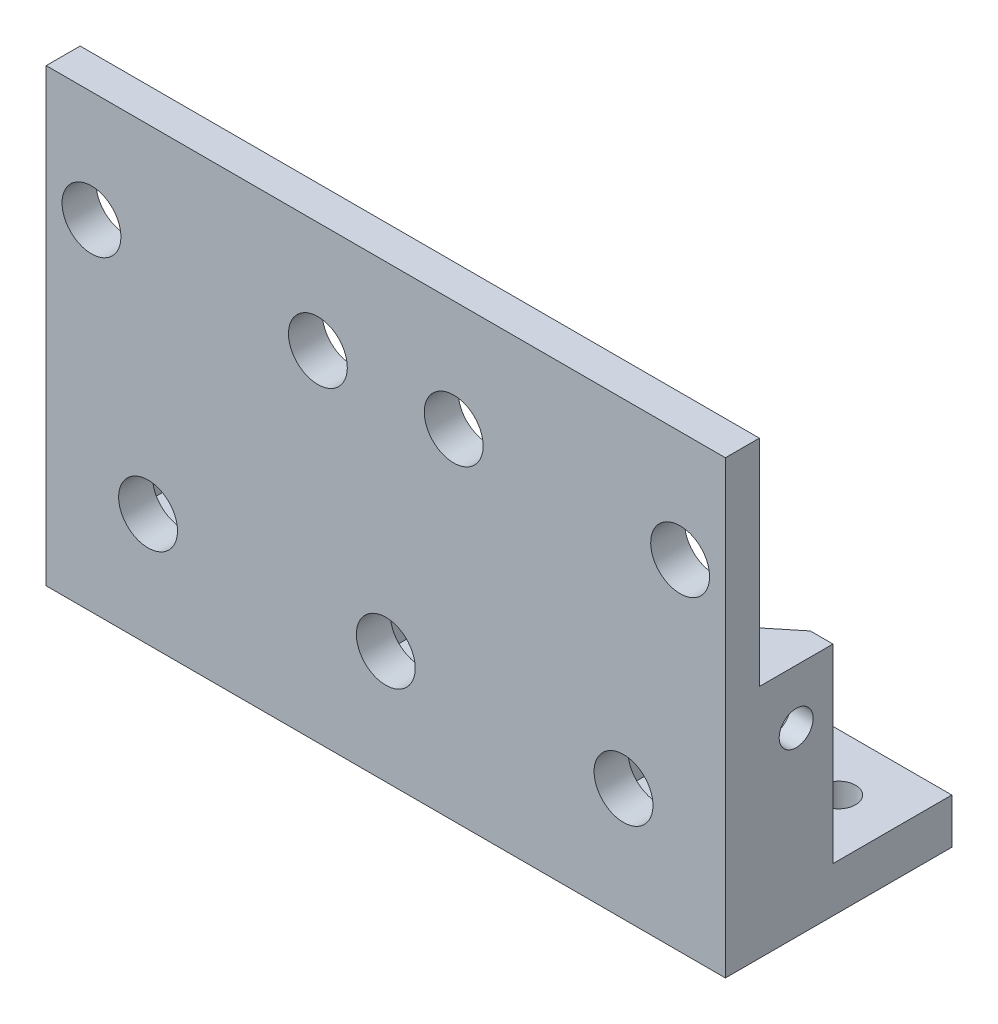
SolidWorks part; units mm, degrees
ref_plane "前视基准面" through (0, 0, 0) normal (0, 0, 1) x (1, 0, 0)
ref_plane "上视基准面" through (0, 0, 0) normal (0, 1, 0) x (1, 0, 0)
ref_plane "右视基准面" through (0, 0, 0) normal (1, 0, 0) x (0, 0, -1)
other "Configuration Table"
sketch "草图1" plane through (0, 0, 0) normal (1, 0, 0) x (0, 0, -1)
  line L1 (-1.5, 19.9) -> (1.5, 19.9)
  line L2 (-1.5, 19.9) -> (-1.5, -19.9)
  line L3 (-1.5, -19.9) -> (1.5, -19.9)
  line L4 (1.5, 19.9) -> (1.5, -0.1)
  line L5 (-1.5, 19.9) -> (1.5, -19.9) construction
  line L6 (-1.5, -19.9) -> (1.5, 19.9) construction
  line L8 (1.5, -19.9) -> (18.5, -19.9)
  line L11 (18.5, -19.9) -> (18.5, -15.9)
  line L12 (18.5, -15.9) -> (1.5, -0.1)
  point P0 (0, 0)
  dimension "D1" = 3
  dimension "D2" = 39.8
  dimension "D3" = 20
  dimension "D4" = 4
  dimension "D5" = 20
extrude "凸台-拉伸1" add sketch "草图1" along normal blind 60
ref_plane "基准面1" through (0, -15.9, 0) normal (0, -1, 0) x (-1, 0, 0)
sketch "草图2" plane through (0, -15.9, 0) normal (0, -1, 0) x (-1, 0, 0)
  line L1 (-60, 18.5) -> (-45, 18.5)
  line L2 (-60, 18.5) -> (-60, 1.5)
  line L3 (-60, 1.5) -> (-45, 1.5)
  line L4 (-45, 18.5) -> (-45, 1.5)
  line L5 (0, 18.5) -> (-15, 18.5)
  line L6 (0, 18.5) -> (0, 1.5)
  line L7 (0, 1.5) -> (-15, 1.5)
  line L8 (-15, 18.5) -> (-15, 1.5)
  line L13 (-30, 18.5) -> (-30, -1.5) construction
  line L14 (-60, 18.5) -> (0, 18.5) construction
  line L15 (-60, 1.5) -> (0, 1.5) construction
  line L16 (-60, -1.5) -> (0, -1.5) construction
  line L18 (-36, 1.5) -> (-24, 1.5)
  line L19 (-36, 1.5) -> (-36, 18.5)
  line L20 (-36, 18.5) -> (-24, 18.5)
  line L21 (-24, 1.5) -> (-24, 18.5)
  line L22 (-36, 1.5) -> (-24, 18.5) construction
  line L23 (-36, 18.5) -> (-24, 1.5) construction
  point P16 (-30, 10)
  dimension "D1" = 15
  dimension "D2" = 12
  dimension "D3" = 15
extrude "切除-拉伸1" cut sketch "草图2" against normal blind 60
hole_wizard "孔1" positions "草图3" profile "草图4" legacy end condition through all
sketch "草图3" plane through (0, 0, -1.5) normal (0, 0, -1) x (-1, 0, 0)
  line L2 (-60, -19.9) -> (0, -19.9) construction
  line L3 (-60, -15.9) -> (-60, 19.9) construction
  line L4 (0, -15.9) -> (0, 19.9) construction
  line L5 (-24, -0.1) -> (-24, -15.9) construction
  point P0 (-51, -9.9)
  point P2 (-30, -9.9)
  point P4 (-9, -9.9)
  dimension "D1" = 10
  dimension "D2" = 10
  dimension "D3" = 10
  dimension "D4" = 9
  dimension "D5" = 9
  dimension "D6" = 6
sketch "草图4" plane through (51, -9.9, -1.5) normal (1, 0, 0) x (0, 1, 0)
  line L0 (0, 0) -> (0, 3)
  line L1 (0, 3) -> (2.6, 3)
  line L2 (2.6, 3) -> (2.6, 0)
  line L3 (2.6, 0) -> (0, 0)
  line L4 (0, 110) -> (0, -10) construction
  dimension "直径" = 5.2
  dimension "深度" = 3
hole_wizard "孔2" positions "草图5" profile "草图6" legacy end condition through all
sketch "草图5" plane through (0, -19.9, 0) normal (0, -1, 0) x (-1, 0, 0)
  line L0 (-60, 18.5) -> (0, 18.5) construction
  line L1 (-60, -1.5) -> (-60, 18.5) construction
  line L2 (0, -1.5) -> (0, 18.5) construction
  point P0 (-55, 13.5)
  point P2 (-30, 13.5)
  point P4 (-5, 13.5)
  dimension "D1" = 5
  dimension "D2" = 5
  dimension "D3" = 5
  dimension "D4" = 5
  dimension "D5" = 5
sketch "草图6" plane through (55, -19.9, -13.5) normal (1, 0, 0) x (0, 0, -1)
  line L0 (0, 0) -> (0, 39.8)
  line L1 (0, 39.8) -> (1.5, 39.8)
  line L2 (1.5, 39.8) -> (1.5, 0)
  line L3 (1.5, 0) -> (0, 0)
  line L4 (0, 110) -> (0, -10) construction
  dimension "直径" = 3
  dimension "深度" = 39.8
sketch "草图7" plane through (0, 0, 0) normal (-1, 0, 0) x (0, 0, 1)
  line L0 (-1.5, -0.1) -> (-1.5, -15.9) construction
  line L1 (-1.5, -0.9) -> (-8, -0.9)
  line L2 (-1.5, -0.9) -> (-1.5, -6.9)
  line L4 (-8, -0.9) -> (-8, -6.9)
  line L5 (-14.212, -15.9) -> (14.212, -15.9) construction
  line L6 (-8, -3.9) -> (-1.5, -3.9) construction
  line L8 (-8, -6.9) -> (-8, -15.9)
  line L9 (-1.5, -15.9) -> (-18.5, -15.9) construction
  line L11 (-8, -15.9) -> (-1.5, -15.9)
  line L12 (-1.5, -6.9) -> (-1.5, -15.9)
  circle A0 centre (-4.75, -3.9) radius 1.5
  dimension "D2" = 3
  dimension "D1" = 15
  dimension "D3" = 6.5
extrude "凸台-拉伸2" add sketch "草图7" against normal blind 2
ref_plane "基准面2" through (30, 0, 0) normal (-1, 0, 0) x (0, 0, 1)
sketch "草图8" plane through (0, -0.9, 0) normal (0, 1, 0) x (1, 0, 0)
  line L0 (2, 8) -> (10, 1.5)
  line L1 (0, 8) -> (2, 8)
  line L2 (0, 8) -> (0, 1.5)
  line L3 (0, 1.5) -> (2, 1.5)
  line L5 (60, 1.5) -> (0, 1.5) construction
  line L6 (10, 1.5) -> (2, 1.5)
  dimension "D1" = 10
extrude "凸台-拉伸3" add sketch "草图8" along normal blind 1.8
hole_wizard "孔3" positions "3D草图1" profile "草图9" legacy end condition through all
sketch3d "3D草图1"
  line L0 (60, -15.9, -1.5) -> (60, 19.9, -1.5) construction
  line L1 (60, 19.9, -1.5) -> (0, 19.9, -1.5) construction
  point P0 (56, 10.1, -1.5)
  point P2 (36, 10.1, -1.5)
  point P16 (24, 10.1, -1.5)
  point P17 (4, 10.1, -1.5)
  dimension "D1" = 4
  dimension "D2" = 24
  dimension "D3" = 9.8
  dimension "D4" = 9.8
sketch "草图9" plane through (56, 10.1, -1.5) normal (1, 0, 0) x (0, 1, 0)
  line L0 (0, 0) -> (0, 3)
  line L1 (0, 3) -> (2.6, 3)
  line L2 (2.6, 3) -> (2.6, 0)
  line L3 (2.6, 0) -> (0, 0)
  line L4 (0, 110) -> (0, -10) construction
  dimension "直径" = 5.2
  dimension "深度" = 3
mirror "镜向1" about plane through (30, 0, 0) normal (-1, 0, 0) of "凸台-拉伸2", "凸台-拉伸3"
